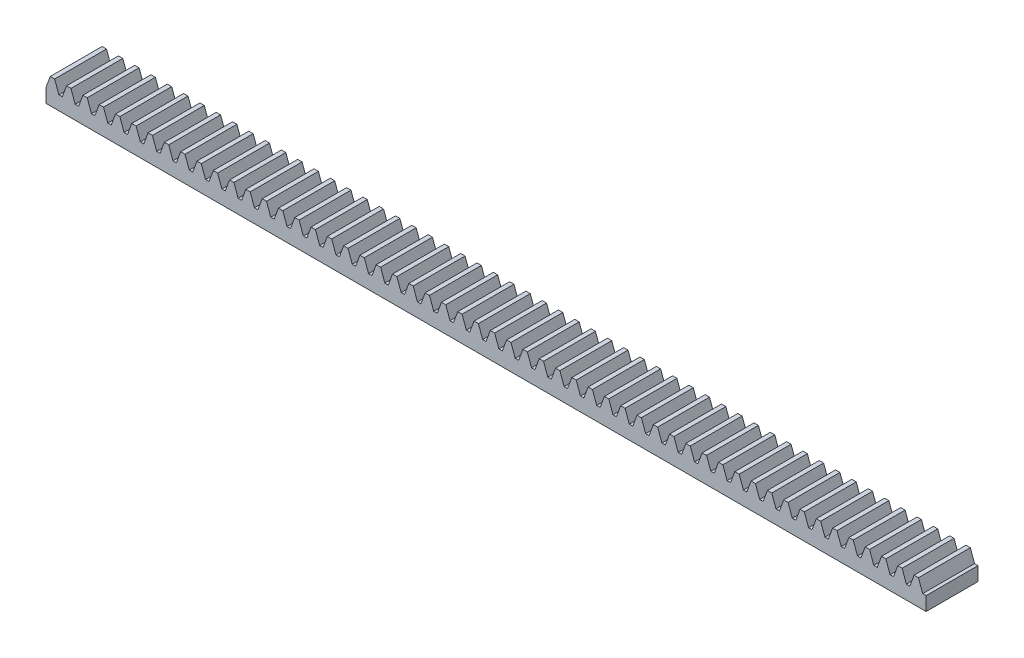
SolidWorks part; units mm, degrees
ref_plane "前视基准面" through (0, 0, 0) normal (0, 0, 1) x (1, 0, 0)
ref_plane "上视基准面" through (0, 0, 0) normal (0, 1, 0) x (1, 0, 0)
ref_plane "右视基准面" through (0, 0, 0) normal (1, 0, 0) x (0, 0, -1)
sketch "草图1" plane through (0, 0, 0) normal (0, 0, 1) x (1, 0, 0)
  line L1 (0, 0) -> (508.938, 0)
  line L2 (0, 0) -> (0, -8)
  line L3 (0, -8) -> (508.938, -8)
  line L4 (508.938, 0) -> (508.938, -8)
  dimension "D1" = 8
  dimension "L" = 508.938
extrude "拉伸1" add sketch "草图1" along normal blind 30
sketch "草图2" plane through (0, 0, 30) normal (0, 0, 1) x (1, 0, 0)
  line L0 (0, 0) -> (2.4568, 6.75)
  line L1 (2.4568, 6.75) -> (4.9854, 6.75)
  line L2 (4.9854, 6.75) -> (7.4422, 0)
  line L3 (508.938, 0) -> (0, 0) construction
  line L4 (0, 0) -> (7.4422, 0)
  line L5 (1.3649, 3.75) -> (6.0773, 3.75) construction
  dimension "D2" = 70
  dimension "alpha" = 110
  dimension "ha" = 3
  dimension "hf" = 3.75
  dimension "S" = 4.7124
extrude "拉伸2" add sketch "草图2" against normal up to surface (30 mm away) up to face at (254.469, -4, 0)
pattern_linear "阵列(线性)1" count 54 spacing 9.4248 along (1, 0, 0) of "拉伸2"
sketch "草图3" plane through (0, 0, 0) normal (0, 1, 0) x (1, 0, 0)
  line L0 (508.938, -15) -> (0, -15) construction
  line L1 (508.938, -30) -> (508.938, 0) construction
  line L2 (0, -30) -> (0, 0) construction
  circle A0 centre (125.513, -15) radius 3.15
  circle A1 centre (245.513, -15) radius 3.15
  point P10 (125.513, -15)
  point P11 (0, 0)
  dimension "D1" = 6.3
  dimension "D2" = 120
equation "\"d\"=\"S@草图2\" * 2"
equation "\"z\"= int(  \"L@草图1\" / (  \"S@草图2\" * 2 ) + 0.5 )"
